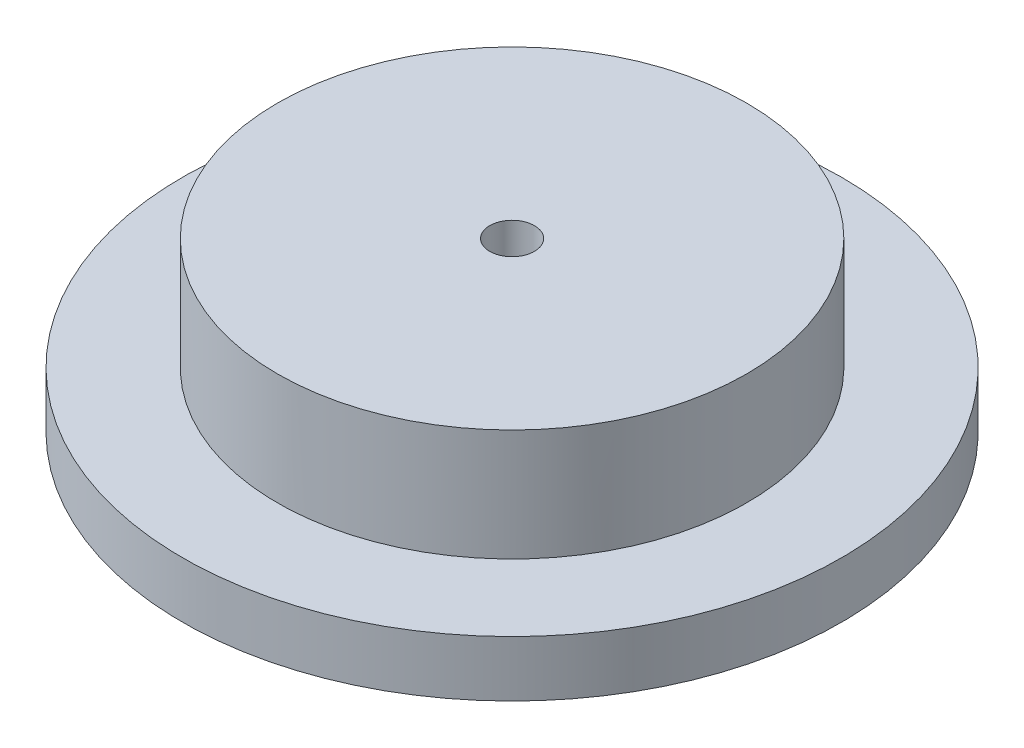
SolidWorks part; units mm, degrees
ref_plane "Front Plane" through (0, 0, 0) normal (0, 0, 1) x (1, 0, 0)
ref_plane "Top Plane" through (0, 0, 0) normal (0, 1, 0) x (1, 0, 0)
ref_plane "Right Plane" through (0, 0, 0) normal (1, 0, 0) x (0, 0, -1)
sketch "Sketch1" plane through (0, 0, 0) normal (0, 1, 0) x (1, 0, 0)
  circle A0 centre (0, 0) radius 2.1
  dimension "D1" = 4.2
extrude "Boss-Extrude1" add sketch "Sketch1" along normal blind 1
sketch "Sketch2" plane through (0, 0, 0) normal (0, -1, 0) x (1, 0, 0)
  circle A0 centre (0, 0) radius 2.95
  dimension "D1" = 5.9
extrude "Boss-Extrude2" add sketch "Sketch2" along normal blind 0.5
sketch "Sketch3" plane through (0, 1, 0) normal (0, 1, 0) x (1, 0, 0)
  circle A0 centre (0, 0) radius 0.2
extrude "Cut-Extrude1" cut sketch "Sketch3" against normal through all
